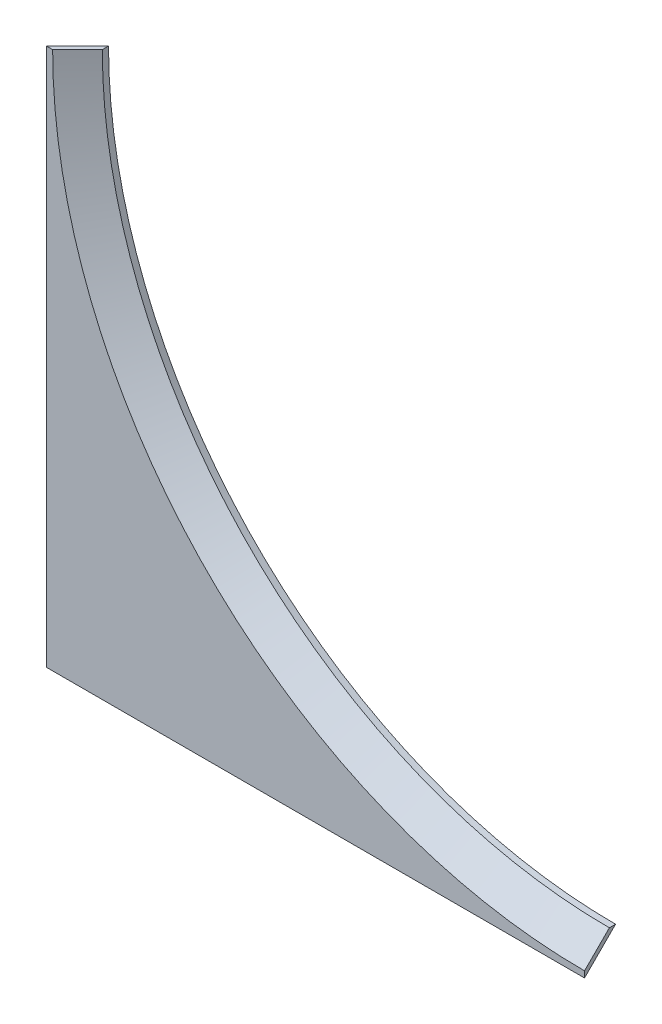
SolidWorks part; units mm, degrees
ref_plane "Front Plane" through (0, 0, 0) normal (0, 0, 1) x (1, 0, 0)
ref_plane "Top Plane" through (0, 0, 0) normal (0, 1, 0) x (1, 0, 0)
ref_plane "Right Plane" through (0, 0, 0) normal (1, 0, 0) x (0, 0, -1)
sketch "Sketch1" plane through (0, 0, 0) normal (0, 0, 1) x (1, 0, 0)
  line L1 (15, 15) -> (260, 15)
  line L2 (15, 15) -> (15, 260)
  arc A0 (15, 260) -> (260, 15) centre (260, 260) ccw
  dimension "D2" = 245
extrude "Boss-Extrude1" add sketch "Sketch1" along normal blind 15
sketch "Sketch2" plane through (0, 15, 0) normal (0, -1, 0) x (1, 0, 0)
  line L0 (15, 0) -> (0, 15)
  line L1 (0, 15) -> (15, 15)
  line L2 (15, 15) -> (15, 0)
extrude "Boss-Extrude2" add sketch "Sketch2" against normal blind 245
ref_plane "Plane1" through (260, 0, 0) normal (-1, 0, 0) x (0, 0, -1)
ref_plane "Plane2" through (147.0152, 682.8495, -546.2189) normal (1, 0, 0) x (0, 0, -1)
ref_plane "Plane3" through (15, 0, 0) normal (1, 0, 0) x (0, 0, -1)
sketch "Sketch3" plane through (15, 0, 0) normal (1, 0, 0) x (0, 0, -1)
  line L0 (0, 15) -> (-15, 0)
  line L1 (-15, 0) -> (-15, 15)
  line L2 (-15, 15) -> (0, 15)
extrude "Boss-Extrude3" add sketch "Sketch3" along normal blind 245
sketch "Sketch4" plane through (15, 0, 0) normal (-1, 0, 0) x (0, 0, 1)
  line L3 (15, 15) -> (0, 15)
  line L4 (0, 15) -> (15, 0)
  line L5 (15, 0) -> (15, 15)
  line L6 (15, 15) -> (0, 15)
  line L7 (0, 15) -> (15, 0)
  line L8 (15, 0) -> (15, 15)
  dimension "D1" = 0
extrude "Boss-Extrude4" add sketch "Sketch4" along normal blind 245
sketch "Sketch5" plane through (0, 15, 0) normal (0, 1, 0) x (1, 0, 0)
  line L4 (0, -15) -> (15, 0)
  line L5 (15, 0) -> (-230, 0)
  line L6 (-230, 0) -> (-230, -15)
  line L7 (-230, -15) -> (0, -15)
  line L8 (0, -15) -> (15, 0)
  line L9 (15, 0) -> (-230, 0)
  line L10 (-230, 0) -> (-230, -15)
  line L11 (-230, -15) -> (0, -15)
  dimension "D1" = 0
extrude "Cut-Extrude1" cut sketch "Sketch5" against normal blind 245
chamfer "Chamfer1" distance 12 angle 45 1 edges at (86.7588, 86.7588, 15)
